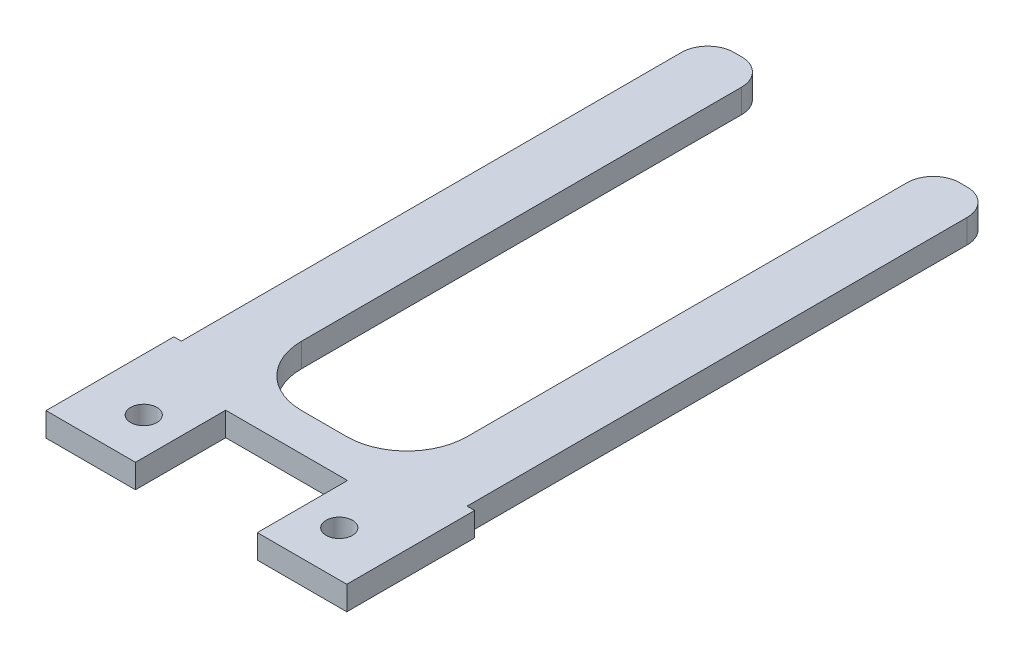
SolidWorks part; units mm, degrees
ref_plane "Alzado" through (0, 0, 0) normal (0, 0, 1) x (1, 0, 0)
ref_plane "Planta" through (0, 0, 0) normal (0, 1, 0) x (1, 0, 0)
ref_plane "Vista lateral" through (0, 0, 0) normal (1, 0, 0) x (0, 0, -1)
sketch "Croquis1" plane through (0, 0, 0) normal (0, 1, 0) x (1, 0, 0)
  line L0 (8.1, 0) -> (-8.1, 0)
  line L1 (-8.1, 0) -> (-8.1, -12)
  line L2 (-8.1, -12) -> (-20, -12)
  line L3 (-20, -12) -> (-20, 5)
  line L4 (-20, 5) -> (-19, 5)
  line L5 (-19, 5) -> (-19, 71.5)
  line L6 (-15.5, 75) -> (-14.5, 75)
  line L7 (-11, 71.5) -> (-11, 5)
  line L8 (-11, 5) -> (11, 5)
  line L9 (0, 5) -> (0, 0)
  line L10 (0, 20.5) -> (0, -26.8333) construction
  line L11 (-20, -6) -> (-8.1, -6) construction
  line L12 (11, 71.5) -> (11, 5)
  line L13 (15.5, 75) -> (14.5, 75)
  line L14 (19, 5) -> (19, 71.5)
  line L15 (20, 5) -> (19, 5)
  line L16 (20, -12) -> (20, 5)
  line L17 (8.1, -12) -> (20, -12)
  line L18 (8.1, 0) -> (8.1, -12)
  circle A0 centre (-13, -6) radius 1.75
  circle A1 centre (13, -6) radius 1.75
  arc A2 (11, 71.5) -> (14.5, 75) centre (14.5, 71.5) cw
  arc A3 (-14.5, 75) -> (-11, 71.5) centre (-14.5, 71.5) cw
  arc A4 (15.5, 75) -> (19, 71.5) centre (15.5, 71.5) cw
  arc A5 (-19, 71.5) -> (-15.5, 75) centre (-15.5, 71.5) cw
  point P29 (11, 75)
  point P32 (-11, 75)
  point P35 (19, 75)
  point P38 (-19, 75)
  point P39 (-8.1, -6)
  dimension "D8" = 3.5
  dimension "D9" = 3.5
  dimension "D1" = 8
  dimension "D2" = 11.9
  dimension "D3" = 20
  dimension "D4" = 19
  dimension "D5" = 5
  dimension "D6" = 17
  dimension "D7" = 70
  dimension "D10" = 4.9
extrude "Saliente-Extruir1" add sketch "Croquis1" along normal mid plane 3.175 contours L0 L18 L17 L16 L15 L14 L13 L12 L8 L9 A1 | L9 L8 L7 L6 L5 L4 L3 L2 L1 L0 A0
fillet "Redondeo1" radius 8 2 edges at (11, 0, -5) (-11, 0, -5)
